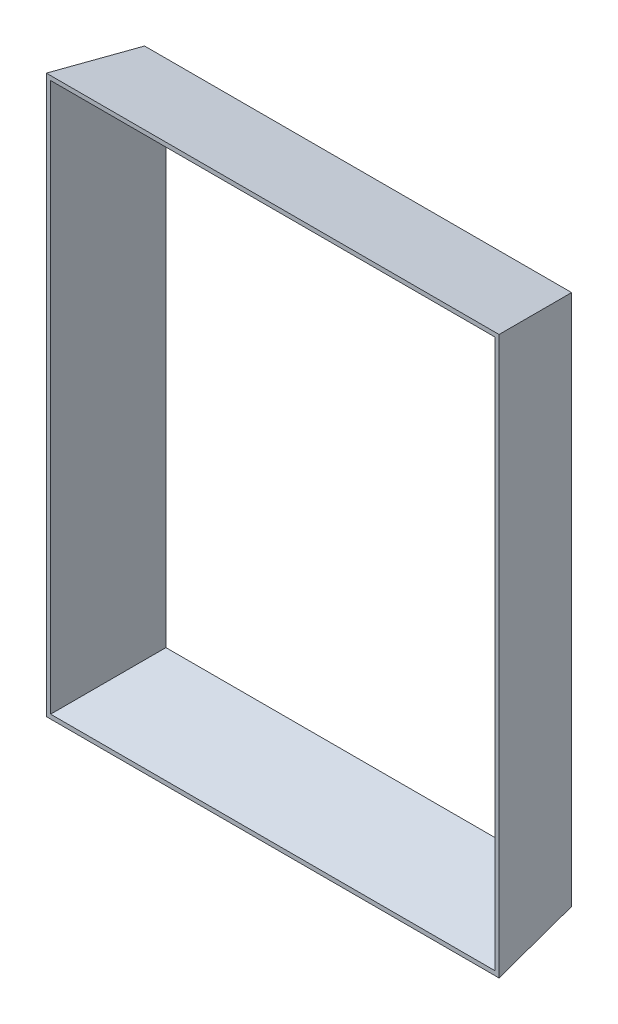
SolidWorks part; units mm, degrees
ref_plane "Front Plane" through (0, 0, 0) normal (0, 0, 1) x (1, 0, 0)
ref_plane "Top Plane" through (0, 0, 0) normal (0, 1, 0) x (1, 0, 0)
ref_plane "Right Plane" through (0, 0, 0) normal (1, 0, 0) x (0, 0, -1)
sketch "Sketch1" plane through (0, 0, 0) normal (0, 0, 1) x (1, 0, 0)
  line L1 (-1254.0257, 611.9277) -> (-254.0257, 611.9277)
  line L2 (-1254.0257, 611.9277) -> (-1254.0257, -633.0723)
  line L3 (-1254.0257, -633.0723) -> (-254.0257, -633.0723)
  line L4 (-254.0257, 611.9277) -> (-254.0257, -633.0723)
  dimension "D1" = 1000
  dimension "D2" = 1245
ref_plane "Plane3" through (0, 0, 200) normal (0, 0, 1) x (1, 0, 0)
sketch "Sketch9" plane through (0, 0, 200) normal (0, 0, 1) x (1, 0, 0)
  line L17 (-224.0257, -663.0723) -> (-224.0257, 641.9277)
  line L18 (-1284.0257, -663.0723) -> (-224.0257, -663.0723)
  line L19 (-1284.0257, 641.9277) -> (-1284.0257, -663.0723)
  line L20 (-224.0257, 641.9277) -> (-1284.0257, 641.9277)
  line L21 (-224.0257, -663.0723) -> (-224.0257, 641.9277)
  line L22 (-1284.0257, -663.0723) -> (-224.0257, -663.0723)
  line L23 (-1284.0257, 641.9277) -> (-1284.0257, -663.0723)
  line L24 (-224.0257, 641.9277) -> (-1284.0257, 641.9277)
  dimension "D1" = 30
loft "Loft1" add profiles "Sketch9", "Sketch1"
sketch "Sketch12" plane through (0, 0, 200) normal (0, 0, 1) x (1, 0, 0)
  line L14 (-1274.0257, 631.9277) -> (-1274.0257, -653.0723)
  line L15 (-234.0257, 631.9277) -> (-1274.0257, 631.9277)
  line L16 (-234.0257, -653.0723) -> (-234.0257, 631.9277)
  line L17 (-1274.0257, -653.0723) -> (-234.0257, -653.0723)
  line L18 (-1274.0257, 631.9277) -> (-1274.0257, -653.0723)
  line L19 (-234.0257, 631.9277) -> (-1274.0257, 631.9277)
  line L20 (-234.0257, -653.0723) -> (-234.0257, 631.9277)
  line L21 (-1274.0257, -653.0723) -> (-234.0257, -653.0723)
  dimension "D1" = 10
sketch "Sketch13" plane through (0, 0, 0) normal (0, 0, 1) x (1, 0, 0)
  line L14 (-1204.0257, -583.0723) -> (-304.0257, -583.0723)
  line L15 (-304.0257, -583.0723) -> (-304.0257, 561.9277)
  line L16 (-1204.0257, 561.9277) -> (-1204.0257, -583.0723)
  line L17 (-304.0257, 561.9277) -> (-1204.0257, 561.9277)
  line L18 (-1204.0257, -583.0723) -> (-304.0257, -583.0723)
  line L19 (-304.0257, -583.0723) -> (-304.0257, 561.9277)
  line L20 (-1204.0257, 561.9277) -> (-1204.0257, -583.0723)
  line L21 (-304.0257, 561.9277) -> (-1204.0257, 561.9277)
  dimension "D1" = 50
loft "Cut-Loft5" cut profiles "Sketch13", "Sketch12"
sketch "Sketch14" plane through (0, 0, 0) normal (0, 0, 1) x (1, 0, 0)
